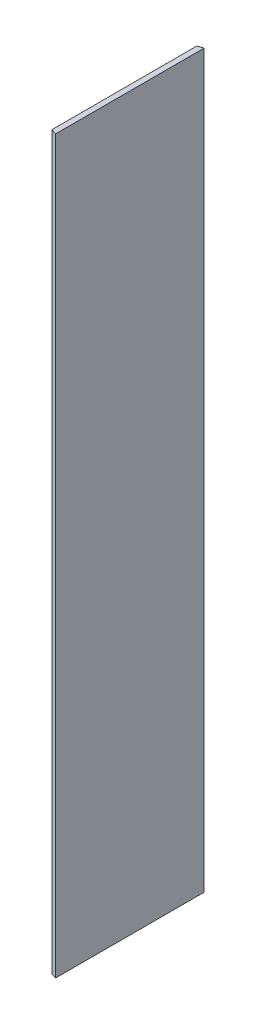
SolidWorks part; units mm, degrees
ref_plane "Спереди" through (0, 0, 0) normal (0, 0, 1) x (1, 0, 0)
ref_plane "Сверху" through (0, 0, 0) normal (0, 1, 0) x (1, 0, 0)
ref_plane "Справа" through (0, 0, 0) normal (1, 0, 0) x (0, 0, -1)
sketch "Эскиз1" plane through (0, 0, 0) normal (0, 1, 0) x (1, 0, 0)
  line L0 (1.0096, -0.8302) -> (1.0096, -106.5801)
  line L1 (1.0096, -106.5801) -> (5.0096, -107.836)
  line L2 (5.0096, -107.836) -> (5.0096, 0.4988)
  line L3 (5.0096, 0.4988) -> (1.0096, -0.8302)
  dimension "D1" = 4
extrude "Вытянуть1" add sketch "Эскиз1" along normal up to surface (533.2137 mm away)
sketch "Эскиз2" plane through (5.0096, 0, 0) normal (1, 0, 0) x (0, 0, -1)
  line L0 (-53.8283, 532.7311) -> (-53.8283, 555.5207) construction
  line L9 (-86.4672, 300.9556) -> (-23.7172, 300.9556)
  line L10 (-91.4672, 295.9556) -> (-91.4672, 145.9556)
  line L11 (-86.4672, 140.9556) -> (-23.7172, 140.9556)
  line L12 (-18.7172, 295.9556) -> (-18.7172, 145.9556)
  arc A4 (-86.4672, 300.9556) -> (-91.4672, 295.9556) centre (-86.4672, 295.9556) ccw
  arc A5 (-18.7172, 295.9556) -> (-23.7172, 300.9556) centre (-23.7172, 295.9556) ccw
  arc A6 (-23.7172, 140.9556) -> (-18.7172, 145.9556) centre (-23.7172, 145.9556) ccw
  arc A7 (-91.4672, 145.9556) -> (-86.4672, 140.9556) centre (-86.4672, 145.9556) ccw
